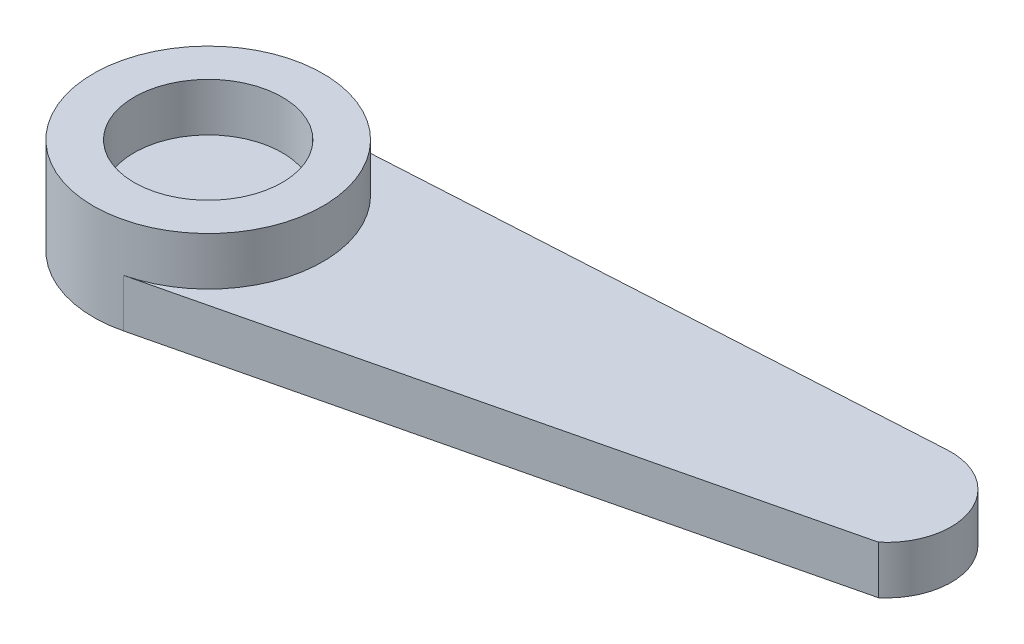
SolidWorks part; units mm, degrees
ref_plane "Front Plane" through (0, 0, 0) normal (0, 0, 1) x (1, 0, 0)
ref_plane "Top Plane" through (0, 0, 0) normal (0, 1, 0) x (1, 0, 0)
ref_plane "Right Plane" through (0, 0, 0) normal (1, 0, 0) x (0, 0, -1)
sketch "Sketch1" plane through (0, 0, 0) normal (0, 1, 0) x (1, 0, 0)
  line L0 (-0.179, 3.0948) -> (15.9324, 4.0265)
  line L1 (0.7251, -3.014) -> (17.1591, 0.9395)
  arc A0 (-0.179, 3.0948) -> (0.7251, -3.014) centre (0, 0) ccw
  arc A1 (17.1591, 0.9395) -> (15.9324, 4.0265) centre (16.0334, 2.2794) ccw
  point P1 (-3.0666, -0.4538)
  point P4 (17.6597, 2.9257)
  dimension "D1" = 3.1
  dimension "D2" = 1.75
  dimension "D3" = 21
extrude "Boss-Extrude1" add sketch "Sketch1" along normal blind 1.3
sketch "Sketch2" plane through (0, 1.3, 0) normal (0, 1, 0) x (1, 0, 0)
  circle A0 centre (0, 0) radius 2
  circle A1 centre (0, 0) radius 3.1
  dimension "D1" = 4
extrude "Boss-Extrude2" add sketch "Sketch2" along normal blind 1.3
